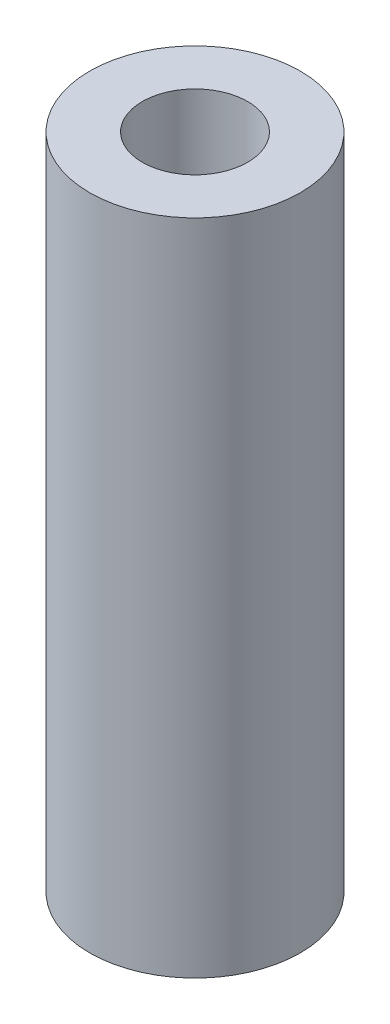
SolidWorks part; units mm, degrees
ref_plane "前视基准面" through (0, 0, 0) normal (0, 0, 1) x (1, 0, 0)
ref_plane "上视基准面" through (0, 0, 0) normal (0, 1, 0) x (1, 0, 0)
ref_plane "右视基准面" through (0, 0, 0) normal (1, 0, 0) x (0, 0, -1)
other "Configuration Table"
sketch "草图1" plane through (0, 0, 0) normal (0, 1, 0) x (1, 0, 0)
  circle A0 centre (0, 0) radius 2
  circle A1 centre (0, 0) radius 4
  dimension "D1" = 4
  dimension "D2" = 2
extrude "凸台-拉伸1" add sketch "草图1" along normal blind 25
